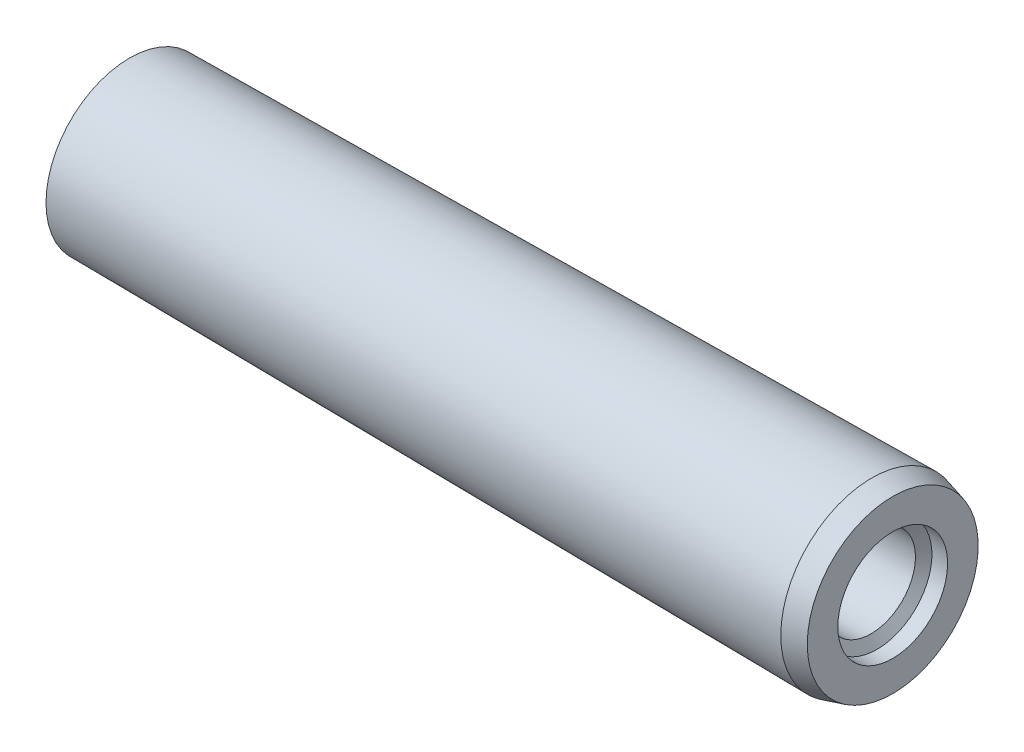
SolidWorks part; units mm, degrees
revolve "Body" add sketch "BodySke" angle 360 about L0
sketch "BodySke" plane through (0, 0, 0) normal (0, 0, 1) x (1, 0, 0)
  line L0 (0, 0) -> (66, 0) construction
  line L1 (0, 0) -> (40, 0) construction
  line L2 (2, 8) -> (73, 8.71)
  line L3 (73, 8.71) -> (75, 8.1741)
  line L4 (0, 0) -> (48.2396, 0)
  line L5 (75, 8.1741) -> (75, 5.25)
  line L6 (75, 5.25) -> (73.5, 5.25)
  line L7 (73.5, 5.25) -> (72.9226, 4.25)
  line L8 (72.9226, 4.25) -> (50, 4.25)
  line L9 (50, 4.25) -> (48.2396, 0)
  line L10 (72, 7) -> (72, 3) construction
  line L11 (59, 16) -> (59, 0) construction
  arc A0 (2, 8) -> (0, 0) centre (17, 0) ccw
  dimension "Crown_ht" = 2
  dimension "D2" = 0.573
  dimension "Diameter" = 16
  dimension "D1" = 75
  dimension "Chamfer_len" = 2
  dimension "Cbore_dia" = 10.5
  dimension "Cbore_dep" = 1.5
  dimension "Tapdrill_dia" = 8.5
  dimension "Tapdrill_dep" = 25
  dimension "D3" = 67.5
  dimension "Length" = 75
  dimension "D4" = 30
  dimension "Advance" = 1.5
  dimension "Thread_dep" = 16
cosmetic thread "ThreadCosmetic" [suppressed] parameters "Depth"=14.5, "Thread_major"=10
ref_plane "Plane1" through (0, 0, 0) normal (0, 0, 1) x (1, 0, 0)
ref_plane "Plane2" through (0, 0, 0) normal (0, 1, 0) x (1, 0, 0)
ref_plane "Plane3" through (0, 0, 0) normal (1, 0, 0) x (0, 0, -1)
sketch "ThdSchSke" plane through (0, 0, 0) normal (0, 0, 1) x (1, 0, 0)
  line L0 (73.3557, 5) -> (73.9354, 4.172)
  line L2 (73.3557, 5) -> (72.7759, 4.172)
  line L3 (72.7759, 4.172) -> (73.9354, 4.172)
  line L4 (73.3557, 5.8566) -> (73.3557, 1.7596) construction
  line L5 (27, 0) -> (36, 0) construction
  line L6 (0, 0) -> (66, 0) construction
  line L7 (75, -8.1741) -> (75, 8.1741) construction
  dimension "D1" = 70
revolve "ThreadSchematic" [suppressed] cut sketch "ThdSchSke" angle 360 about L5
pattern_linear "ThdSchPat" [suppressed]
equation "' \"Diameter@BodySke\" = 16"
equation "' \"Crown_ht@BodySke\" = 2"
equation "' \"Thread_major@ThreadCosmetic\"  = 10"
equation "' \"Thread_major@ThreadCosmetic\" = 10"
equation "' \"Advance@BodySke\" = 1.5"
equation "' \"Cbore_dia@BodySke\" = 10.5"
equation "' \"Thread_dep@BodySke\"  = 16"
equation "' \"Thread_dep@BodySke\" = 16"
equation "' \"Tapdrill_dep@BodySke\" = 25"
equation "' \"Cbore_dep@BodySke\" = 1.5"
equation "' \"Tapdrill_dia@BodySke\" = 8.5"
equation "' \"Thread_minor@ThdSchSke\" = 8.344"
equation "'  \"Length@BodySke\" = 75"
equation "\"Chamfer_len@BodySke\" = \"Crown_ht@BodySke\""
equation "\"Depth@ThreadCosmetic\" = \"Thread_dep@BodySke\"  -  \"Cbore_dep@BodySke\""
equation "\"Thread_nominal@ThdSchSke\" = \"Thread_major@ThreadCosmetic\""
equation "\"Inset@ThdSchSke\" = \"Cbore_dep@BodySke\" + (\"Cbore_dia@BodySke\" - \"Thread_major@ThreadCosmetic\") / 2 * tan(30 * 0.0174533)"
equation "\"Num_threads@ThdSchPat\" = int(  ( \"Thread_dep@BodySke\"  - \"Inset@ThdSchSke\" ) / \"Advance@BodySke\" + 0.999 )  + 1"
equation "\"Advance@ThdSchPat\" = (  \"Thread_dep@BodySke\" - \"Inset@ThdSchSke\" ) /  (\"Num_threads@ThdSchPat\" - 1) 'relax it"
